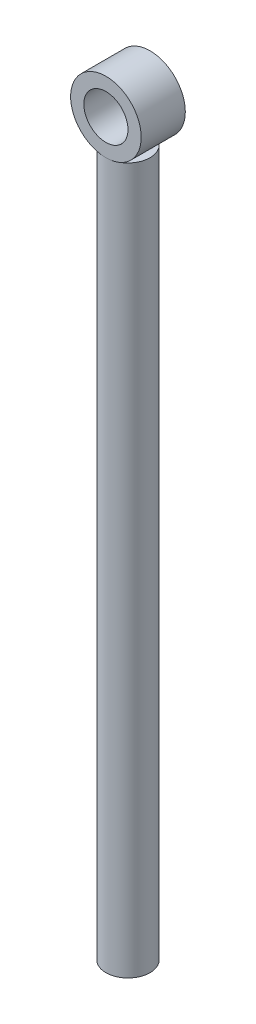
SolidWorks part; units mm, degrees
ref_plane "Front Plane" through (0, 0, 0) normal (0, 0, 1) x (1, 0, 0)
ref_plane "Top Plane" through (0, 0, 0) normal (0, 1, 0) x (1, 0, 0)
ref_plane "Right Plane" through (0, 0, 0) normal (1, 0, 0) x (0, 0, -1)
sketch "Sketch1" plane through (0, 0, 0) normal (0, 1, 0) x (1, 0, 0)
  circle A1 centre (0, 0) radius 3.175
  dimension "D1" = 6.35
extrude "Boss-Extrude1" add sketch "Sketch1" along normal mid plane 101.6
sketch "Sketch2" plane through (0, 0, 0) normal (0, 0, 1) x (1, 0, 0)
  line L0 (3.175, 50.8) -> (-3.175, 50.8) construction
  circle A0 centre (0, 55.88) radius 5.08
  circle A1 centre (0, 55.88) radius 3.175
  dimension "D1" = 10.16
  dimension "D2" = 6.35
extrude "Boss-Extrude2" add sketch "Sketch2" along normal mid plane 6.35 separate body
